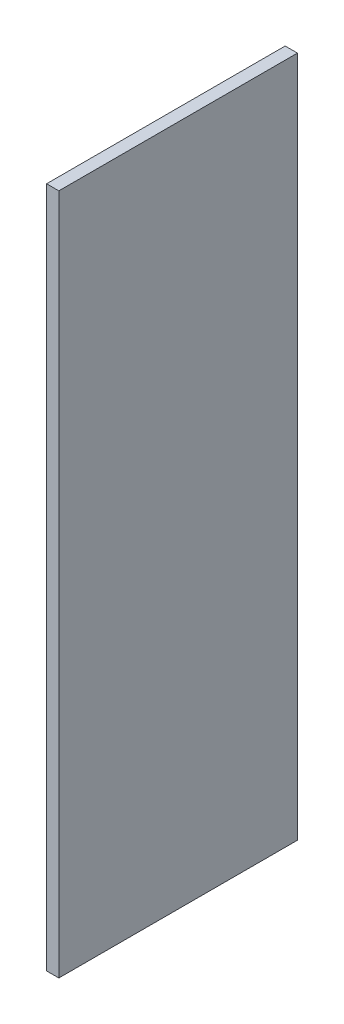
SolidWorks part; units mm, degrees
material "Pine"
ref_plane "Front Plane" through (0, 0, 0) normal (0, 0, 1) x (1, 0, 0)
ref_plane "Top Plane" through (0, 0, 0) normal (0, 1, 0) x (1, 0, 0)
ref_plane "Right Plane" through (0, 0, 0) normal (1, 0, 0) x (0, 0, -1)
sketch "Sketch1" plane through (0, 0, 0) normal (1, 0, 0) x (0, 0, -1)
  line L1 (-175, 500) -> (175, 500)
  line L2 (-175, 500) -> (-175, -500)
  line L3 (-175, -500) -> (175, -500)
  line L4 (175, 500) -> (175, -500)
  line L5 (-175, 500) -> (175, -500) construction
  line L6 (-175, -500) -> (175, 500) construction
  point P0 (0, 0)
  dimension "D1" = 350
  dimension "D2" = 1000
extrude "Boss-Extrude1" add sketch "Sketch1" along normal blind 18
